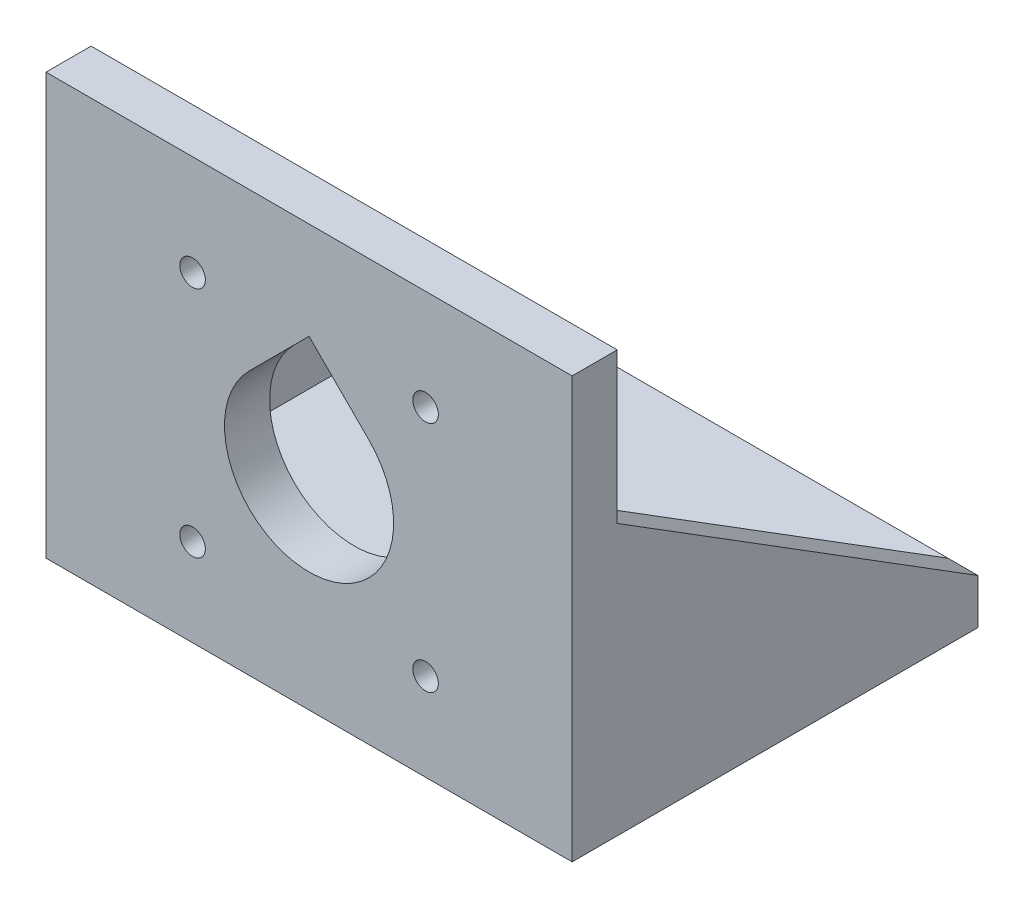
SolidWorks part; units mm, degrees
ref_plane "Спереди" through (0, 0, 0) normal (0, 0, 1) x (1, 0, 0)
ref_plane "Сверху" through (0, 0, 0) normal (0, 1, 0) x (1, 0, 0)
ref_plane "Справа" through (0, 0, 0) normal (1, 0, 0) x (0, 0, -1)
other "Configuration Table"
sketch "01_Пластина_эскиз" plane through (0, 0, 0) normal (0, 0, 1) x (1, 0, 0)
  line L1 (0, 0) -> (70, 0)
  line L2 (0, 0) -> (0, 56)
  line L3 (0, 56) -> (70, 56)
  line L4 (70, 0) -> (70, 56)
  dimension "D1" = 70
  dimension "D2" = 56
extrude "01_Передняя_пластина" add sketch "01_Пластина_эскиз" along normal blind 6
sketch "02_Полка_эскиз" plane through (0, 0, 0) normal (0, 1, 0) x (1, 0, 0)
  line L1 (0, 48) -> (70, 48)
  line L2 (0, 48) -> (0, -6)
  line L3 (0, -6) -> (70, -6)
  line L4 (70, 48) -> (70, -6)
  dimension "D1" = 70
  dimension "D2" = 54
  dimension "D3" = 6
extrude "02_Полка" add sketch "02_Полка_эскиз" along normal blind 6
sketch "03_Косынка_левая_эскиз" plane through (0, 0, 0) normal (1, 0, 0) x (0, 0, -1)
  line L0 (48, 6) -> (0, 6)
  line L1 (0, 6) -> (0, 36)
  line L2 (0, 36) -> (48, 6)
  dimension "D3" = 6
  dimension "D1" = 48
  dimension "D2" = 30
extrude "03_Косынка_левая" add sketch "03_Косынка_левая_эскиз" along normal blind 4
sketch "04_Косынка_правая_эскиз" plane through (0, 0, 0) normal (1, 0, 0) x (0, 0, -1)
  line L0 (48, 6) -> (0, 6)
  line L1 (0, 6) -> (0, 36)
  line L2 (0, 36) -> (48, 6)
  dimension "D3" = 6
  dimension "D1" = 48
  dimension "D2" = 30
extrude "04_Косынка_правая" add sketch "04_Косынка_правая_эскиз" along normal blind 4 from offset 66
sketch "05_Мотор_передний_фланец_эскиз" plane through (0, 0, 0) normal (0, 0, 1) x (1, 0, 0)
  line L0 (4, 6) -> (66, 6) construction
  circle A0 centre (35, 27.15) radius 11.25
  circle A1 centre (19.5, 11.65) radius 1.7
  circle A2 centre (19.5, 42.65) radius 1.7
  circle A3 centre (50.5, 11.65) radius 1.7
  circle A4 centre (50.5, 42.65) radius 1.7
  dimension "D1" = 3.4
  dimension "D2" = 3.4
  dimension "D3" = 3.4
  dimension "D4" = 3.4
  dimension "D5" = 22.5
  dimension "D6" = 15.5
  dimension "D7" = 31
  dimension "D8" = 15.5
  dimension "D9" = 31
  dimension "D10" = 35
  dimension "D11" = 21.15
extrude "05_Буртик_и_4_отверстия_М3" cut sketch "05_Мотор_передний_фланец_эскиз" against normal through all and the other way through all
sketch "06_Свод_45град_эскиз" plane through (0, 0, 0) normal (0, 0, 1) x (1, 0, 0)
  line L0 (27.045, 35.105) -> (42.955, 35.105)
  line L1 (42.955, 35.105) -> (35, 43.0599)
  line L2 (35, 43.0599) -> (27.045, 35.105)
  circle A0 centre (35, 27.15) radius 11.25 construction
  dimension "D1" = 7.955
  dimension "D2" = 15.9099
  dimension "D3" = 7.955
  dimension "D4" = 35
extrude "06_Свод_отверстия_для_печати" cut sketch "06_Свод_45град_эскиз" against normal through all and the other way through all
sketch "07_Крепление_полки_эскиз" plane through (0, 0, 0) normal (0, 1, 0) x (1, 0, 0)
  circle A0 centre (8.5, 12) radius 2.25
  circle A1 centre (8.5, 38) radius 2.25
  circle A2 centre (61.5, 12) radius 2.25
  circle A3 centre (61.5, 38) radius 2.25
  dimension "D1" = 4.5
  dimension "D2" = 4.5
  dimension "D3" = 4.5
  dimension "D4" = 4.5
  dimension "D5" = 53
  dimension "D6" = 26
  dimension "D7" = 8.5
  dimension "D8" = 12
extrude "07_4_отверстия_М4" cut sketch "07_Крепление_полки_эскиз" against normal through all and the other way through all
equation "\"Ширина\"= 70"
equation "\"Высота пластины\"= 56"
equation "\"Толщина стенок\"= 6"
equation "\"Длина полки\"= 48"
equation "\"Толщина косынки\"= 4"
equation "\"Высота косынки\"= 30"
equation "\"Высота оси\"= 30"
equation "\"Шаг М3 ПРЕДВ\"= 31"
equation "\"Отверстие буртика\"= 22.5"
equation "\"Отверстия М3\"= 3.4"
equation "\"Отверстия М4\"= 4.5"
equation "\"Отступ М4 сбоку\"= 8.5"
equation "\"Ближний ряд М4\"= 12"
equation "\"Отступ М4 сзади\"= 10"
equation "\"D1@01_Пластина_эскиз\" = \"Ширина\""
equation "\"D2@01_Пластина_эскиз\" = \"Высота пластины\""
equation "\"D1@01_Передняя_пластина\" = \"Толщина стенок\""
equation "\"D1@02_Полка_эскиз\" = \"Ширина\""
equation "\"D2@02_Полка_эскиз\" = \"Длина полки\" + \"Толщина стенок\""
equation "\"D1@02_Полка\" = \"Толщина стенок\""
equation "\"D1@03_Косынка_левая_эскиз\" = \"Длина полки\""
equation "\"D2@03_Косынка_левая_эскиз\" = \"Высота косынки\""
equation "\"D1@03_Косынка_левая\" = \"Толщина косынки\""
equation "\"D1@04_Косынка_правая_эскиз\" = \"Длина полки\""
equation "\"D2@04_Косынка_правая_эскиз\" = \"Высота косынки\""
equation "\"D1@04_Косынка_правая\" = \"Толщина косынки\""
equation "\"D19@04_Косынка_правая\" = \"Ширина\" - \"Толщина косынки\""
equation "\"D1@05_Мотор_передний_фланец_эскиз\" = \"Отверстия М3\""
equation "\"D2@05_Мотор_передний_фланец_эскиз\" = \"Отверстия М3\""
equation "\"D3@05_Мотор_передний_фланец_эскиз\" = \"Отверстия М3\""
equation "\"D4@05_Мотор_передний_фланец_эскиз\" = \"Отверстия М3\""
equation "\"D5@05_Мотор_передний_фланец_эскиз\" = \"Отверстие буртика\""
equation "\"D6@05_Мотор_передний_фланец_эскиз\" = \"Шаг М3 ПРЕДВ\" / 2"
equation "\"D7@05_Мотор_передний_фланец_эскиз\" = \"Шаг М3 ПРЕДВ\""
equation "\"D8@05_Мотор_передний_фланец_эскиз\" = \"Шаг М3 ПРЕДВ\" / 2"
equation "\"D9@05_Мотор_передний_фланец_эскиз\" = \"Шаг М3 ПРЕДВ\""
equation "\"D1@06_Свод_45град_эскиз\" = \"Отверстие буртика\" / (2 * SQR(2))"
equation "\"D2@06_Свод_45град_эскиз\" = \"Отверстие буртика\" / SQR(2)"
equation "\"D3@06_Свод_45град_эскиз\" = \"Отверстие буртика\" / (2 * SQR(2))"
equation "\"D1@07_Крепление_полки_эскиз\" = \"Отверстия М4\""
equation "\"D2@07_Крепление_полки_эскиз\" = \"Отверстия М4\""
equation "\"D3@07_Крепление_полки_эскиз\" = \"Отверстия М4\""
equation "\"D4@07_Крепление_полки_эскиз\" = \"Отверстия М4\""
equation "\"D5@07_Крепление_полки_эскиз\" = \"Ширина\" - 2 * \"Отступ М4 сбоку\""
equation "\"D6@07_Крепление_полки_эскиз\" = \"Длина полки\" - \"Ближний ряд М4\" - \"Отступ М4 сзади\""
equation "\"D3@02_Полка_эскиз\" = \"Толщина стенок\""
equation "\"D3@03_Косынка_левая_эскиз\" = \"Толщина стенок\""
equation "\"D3@04_Косынка_правая_эскиз\" = \"Толщина стенок\""
equation "\"D10@05_Мотор_передний_фланец_эскиз\" = \"Ширина\" / 2"
equation "\"D4@06_Свод_45град_эскиз\" = \"Ширина\" / 2"
equation "\"D7@07_Крепление_полки_эскиз\" = \"Отступ М4 сбоку\""
equation "\"D8@07_Крепление_полки_эскиз\" = \"Ближний ряд М4\""
